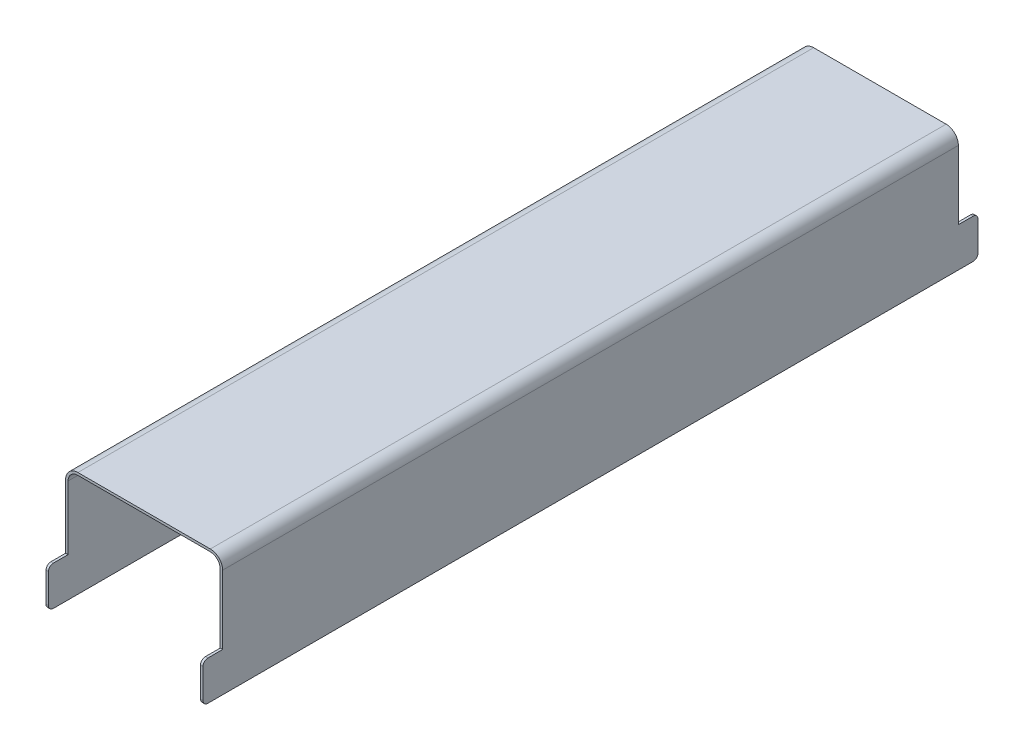
SolidWorks part; units mm, degrees
ref_plane "Front Plane" through (0, 0, 0) normal (0, 0, 1) x (1, 0, 0)
ref_plane "Top Plane" through (0, 0, 0) normal (0, 1, 0) x (1, 0, 0)
ref_plane "Right Plane" through (0, 0, 0) normal (1, 0, 0) x (0, 0, -1)
sketch "Sketch2" plane through (0, 0, 0) normal (0, 0, 1) x (1, 0, 0)
  line L0 (15.5, -24) -> (15.5, -2)
  line L1 (13.5, 0) -> (-13.5, 0)
  line L2 (-15.5, -2) -> (-15.5, -23)
  line L3 (16, -24) -> (16, -2)
  line L4 (13.5, 0.5) -> (-13.5, 0.5)
  line L5 (-16, -2) -> (-16, -23)
  line L6 (-16, -23) -> (-15.5, -23)
  line L7 (15.5, -24) -> (16, -24)
  arc A0 (15.5, -2) -> (13.5, 0) centre (13.5, -2) ccw
  arc A1 (-13.5, 0) -> (-15.5, -2) centre (-13.5, -2) ccw
  arc A2 (16, -2) -> (13.5, 0.5) centre (13.5, -2) ccw
  arc A3 (-13.5, 0.5) -> (-16, -2) centre (-13.5, -2) ccw
  point P7 (15.5, 0)
  point P10 (-15.5, 0)
  dimension "D4" = 2
  dimension "D1" = 32
  dimension "D2" = 24
  dimension "D3" = 23
  dimension "D5" = 0.5
extrude "Boss-Extrude1" add sketch "Sketch2" along normal mid plane 150 contours L2 L6 L5 A3 L4 A2 L3 L7 L0 A0 L1 A1
ref_plane "Plane2" through (15.75, 0, 0) normal (1, 0, 0) x (0, 0, -1)
sketch "Sketch3" plane through (15.75, 0, 0) normal (1, 0, 0) x (0, 0, -1)
  line L0 (-75, -24) -> (-78, -24)
  line L1 (-79, -23) -> (-79, -17)
  line L2 (-78, -16) -> (-75, -16)
  line L3 (-75, -24) -> (-75, -2) construction
  line L4 (-75, -16) -> (-75, -24)
  line L5 (0, 0) -> (0, -24) construction
  line L6 (-75, 0) -> (75, 0) construction
  line L7 (-75, -24) -> (75, -24) construction
  line L8 (75, -24) -> (78, -24)
  line L9 (75, -16) -> (75, -24)
  line L10 (79, -23) -> (79, -17)
  line L11 (78, -16) -> (75, -16)
  arc A0 (-78, -24) -> (-79, -23) centre (-78, -23) cw
  arc A1 (-78, -16) -> (-79, -17) centre (-78, -17) ccw
  arc A2 (78, -24) -> (79, -23) centre (78, -23) ccw
  arc A3 (79, -17) -> (78, -16) centre (78, -17) ccw
  point P19 (-79, -24)
  point P22 (-79, -16)
  point P25 (79, -24)
  point P28 (79, -16)
  dimension "D3" = 1
  dimension "D4" = 1
  dimension "D1" = 8
  dimension "D2" = 4
extrude "Boss-Extrude2" add sketch "Sketch3" along normal mid plane 0.5
ref_plane "Plane3" through (-15.75, 0, 0) normal (1, 0, 0) x (0, 0, -1)
sketch "Sketch4" plane through (-15.75, 0, 0) normal (1, 0, 0) x (0, 0, -1)
  line L0 (-75, -23) -> (-78, -23)
  line L1 (-79, -22) -> (-79, -16)
  line L2 (-78, -15) -> (-75, -15)
  line L3 (-75, -2) -> (-75, -23) construction
  line L4 (-75, -15) -> (-75, -23)
  line L6 (0, 0) -> (0, -23) construction
  line L7 (-75, -23) -> (75, -23) construction
  line L8 (79, -22) -> (79, -16)
  line L9 (75, -23) -> (78, -23)
  line L10 (75, -15) -> (75, -23)
  line L11 (78, -15) -> (75, -15)
  arc A0 (79, -22) -> (78, -23) centre (78, -22) cw
  arc A1 (79, -16) -> (78, -15) centre (78, -16) ccw
  arc A2 (-78, -23) -> (-79, -22) centre (-78, -22) cw
  arc A3 (-79, -16) -> (-78, -15) centre (-78, -16) cw
  point P18 (79, -23)
  point P21 (79, -15)
  point P24 (-79, -23)
  point P27 (-79, -15)
  dimension "D3" = 1
  dimension "D1" = 8
  dimension "D2" = 4
extrude "Boss-Extrude3" add sketch "Sketch4" along normal mid plane 0.5
